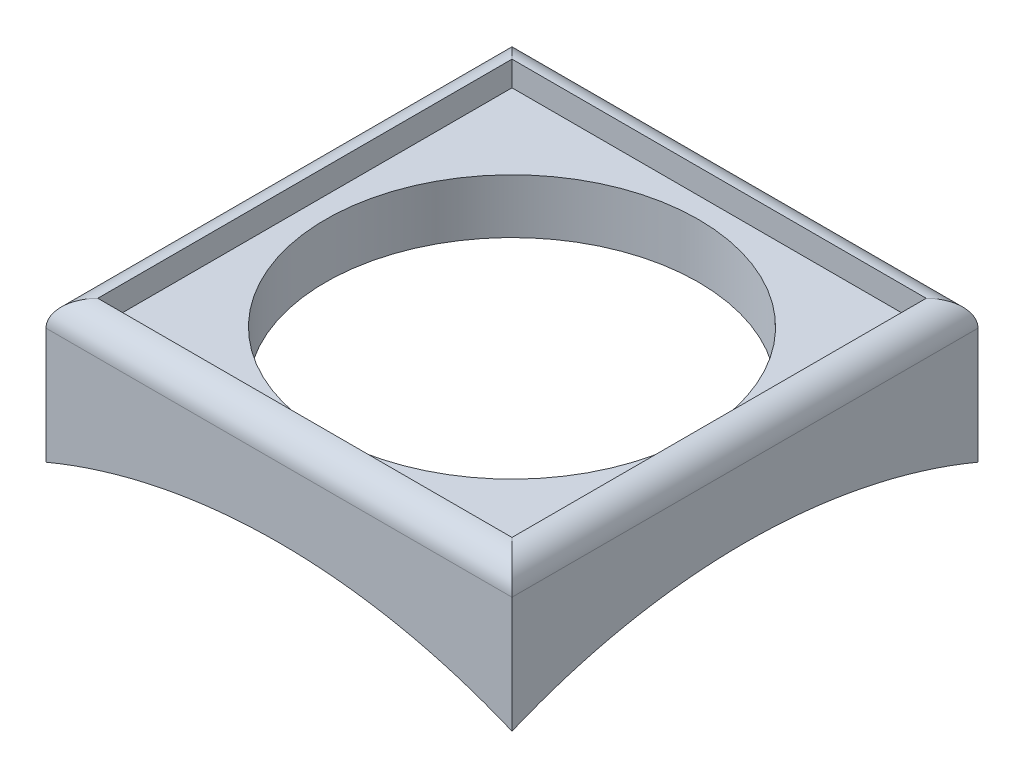
SolidWorks part; units mm, degrees
ref_plane "前视基准面" through (0, 0, 0) normal (0, 0, 1) x (1, 0, 0)
ref_plane "上视基准面" through (0, 0, 0) normal (0, 1, 0) x (1, 0, 0)
ref_plane "右视基准面" through (0, 0, 0) normal (1, 0, 0) x (0, 0, -1)
sketch "草图1" plane through (0, 0, 0) normal (0, 0, 1) x (1, 0, 0)
  line L1 (-27, 27) -> (27, 27)
  line L2 (-27, 27) -> (-27, -27)
  line L3 (-27, -27) -> (27, -27)
  line L4 (27, 27) -> (27, -27)
  line L5 (-27, 27) -> (27, -27) construction
  line L6 (-27, -27) -> (27, 27) construction
  point P0 (0, 0)
  dimension "D1" = 54
  dimension "D2" = 54
extrude "凸台-拉伸1" add sketch "草图1" along normal mid plane 54
ref_plane "基准面1" through (0, 27, 0) normal (0, 1, 0) x (1, 0, 0)
sketch "草图2" plane through (0, 27, 0) normal (0, 1, 0) x (1, 0, 0)
  line L1 (-9, 9) -> (9, 9)
  line L2 (-9, 9) -> (-9, -9)
  line L3 (-9, -9) -> (9, -9)
  line L4 (9, 9) -> (9, -9)
  line L5 (-9, 9) -> (9, -9) construction
  line L6 (-9, -9) -> (9, 9) construction
  line L7 (-27, -27) -> (27, -27)
  line L8 (-27, -27) -> (-27, 27)
  line L9 (-27, 27) -> (27, 27)
  line L10 (27, -27) -> (27, 27)
  line L11 (-27, -27) -> (27, 27) construction
  line L12 (-27, 27) -> (27, -27) construction
  point P0 (0, 0)
  point P6 (0, 0)
  dimension "D1" = 18
  dimension "D2" = 18
extrude "切除-拉伸1" cut sketch "草图2" against normal blind 54
ref_plane "基准面2" through (0, 0, 9) normal (0, 0, 1) x (1, 0, 0)
sketch "草图3" plane through (0, 0, 9) normal (0, 0, 1) x (1, 0, 0)
  line L0 (9, -27) -> (9, 27) construction
  line L1 (-9, -27) -> (9, -27)
  line L2 (-9, -27) -> (-9, 9)
  line L3 (-9, 9) -> (9, 9)
  line L4 (9, -27) -> (9, 9)
  line L5 (9.9, 27) -> (-9.9, 27) construction
  dimension "D1" = 18
extrude "切除-拉伸2" cut sketch "草图3" against normal through all
sketch "草图4" plane through (0, 0, 0) normal (0, 0, 1) x (1, 0, 0)
  line L0 (0, 25) -> (0, -25)
  arc A0 (0, 25) -> (0, -25) centre (0, 0) ccw
  dimension "D1" = 50
revolve "切除-旋转1" cut sketch "草图4" angle 360 about L0
fillet "圆角1" radius 1 4 edges at (-9, 27, 0) (0, 27, -9) (9, 27, 0) (0, 27, 9)
scale "缩放比例1" scale about origin uniform scaling yes scale factor 2.083333
ref_plane "基准面3" through (0, 56.25, 0) normal (0, 1, 0) x (1, 0, 0)
sketch "草图5" plane through (0, 56.25, 0) normal (0, 1, 0) x (1, 0, 0)
  line L1 (-16.6667, 16.6667) -> (16.6667, 16.6667)
  line L2 (-16.6667, 16.6667) -> (-16.6667, -16.6667)
  line L3 (-16.6667, -16.6667) -> (16.6667, -16.6667)
  line L4 (16.6667, 16.6667) -> (16.6667, -16.6667)
  line L5 (-16.6667, 16.6667) -> (16.6667, -16.6667) construction
  line L6 (-16.6667, -16.6667) -> (16.6667, 16.6667) construction
  point P0 (0, 0)
extrude "切除-拉伸3" cut sketch "草图5" against normal blind 2
ref_plane "基准面4" through (0, 54.25, 0) normal (0, 1, 0) x (1, 0, 0)
sketch "草图6" plane through (0, 54.25, 0) normal (0, 1, 0) x (1, 0, 0)
  circle A0 centre (0, 0) radius 15
  dimension "D1" = 30
extrude "切除-拉伸4" cut sketch "草图6" against normal blind 6
